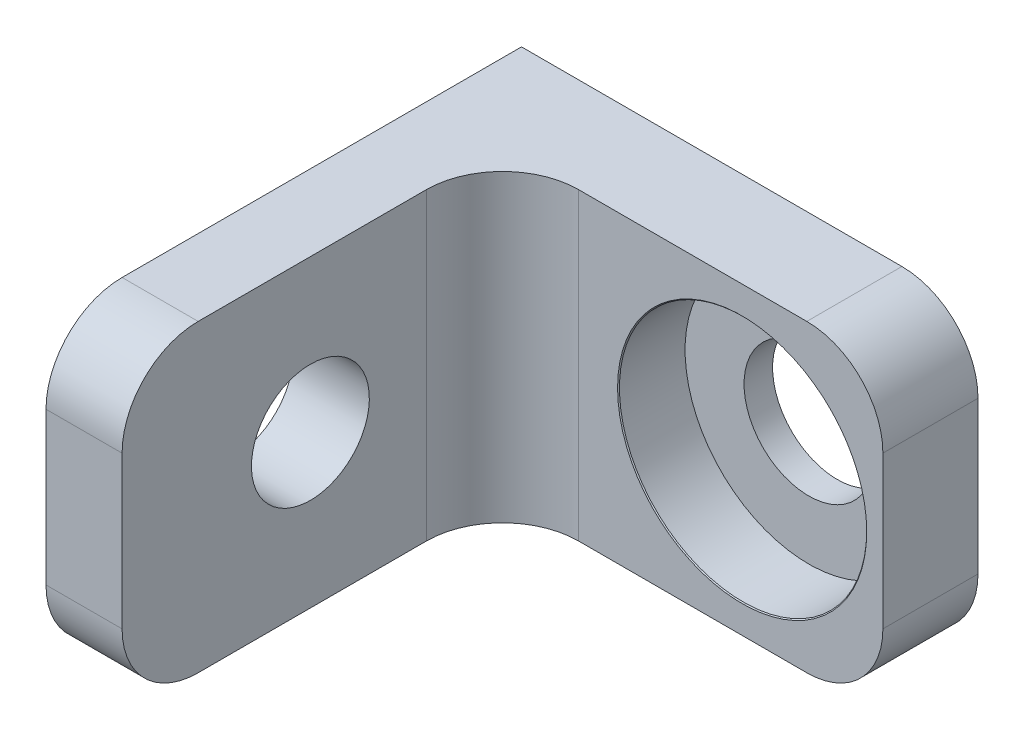
SolidWorks part; units mm, degrees
ref_plane "Plano frontal" through (0, 0, 0) normal (0, 0, 1) x (1, 0, 0)
ref_plane "Plano superior" through (0, 0, 0) normal (0, 1, 0) x (1, 0, 0)
ref_plane "Plano direito" through (0, 0, 0) normal (1, 0, 0) x (0, 0, -1)
sketch "Esboço1" plane through (0, 0, 0) normal (0, 0, 1) x (1, 0, 0)
  line L1 (-12, 6) -> (0, 6)
  line L2 (-12, 6) -> (-12, -2)
  line L3 (-12, -2) -> (0, -2)
  line L4 (0, 6) -> (0, -2)
  dimension "D1" = 8
  dimension "D2" = 12
extrude "Ressalto-extrusão1" add sketch "Esboço1" along normal blind 2.5
sketch "Esboço2" plane through (0, 0, 2.5) normal (0, 0, 1) x (1, 0, 0)
  line L0 (-12, 2) -> (0, 2) construction
  line L1 (-12, 6) -> (-12, -2) construction
  line L2 (0, -2) -> (0, 6) construction
  circle A0 centre (-3.7, 2) radius 1.7
  point P9 (-5.4, 2)
  dimension "D2" = 3.4
  dimension "D1" = 6.6
sketch "Esboço3" plane through (0, 0, 2.5) normal (0, 0, 1) x (1, 0, 0)
  line L0 (-12, -2) -> (0, -2) construction
  line L1 (-12, 6) -> (-10, 6)
  line L2 (-12, 6) -> (-12, -2)
  line L3 (-12, -2) -> (-10, -2)
  line L4 (-10, 6) -> (-10, -2)
  dimension "D1" = 2
extrude "Ressalto-extrusão2" add sketch "Esboço3" along normal blind 10
sketch "Esboço6" plane through (-10, 0, 0) normal (1, 0, 0) x (0, 0, -1)
  line L0 (-12.5, 2) -> (-2.5011, 2) construction
  line L1 (-12.5, -2) -> (-12.5, 6) construction
  line L2 (-2.5, -2) -> (-2.5, 6) construction
  circle A0 centre (-7.55, 2) radius 1.55
  point P6 (-6, 2)
  dimension "D2" = 3.1
  dimension "D1" = 3.5
hole_wizard "Rebaixo para parafuso com cabeça redonda de M33" positions "Esboço9" profile "Esboço10" counterbore size "M3" standard "ISO" end condition through all
sketch "Esboço9" plane through (0, 0, 2.5) normal (0, 0, 1) x (1, 0, 0)
  point P0 (-3.7, 2)
sketch "Esboço10" plane through (-3.7, 2, 2.5) normal (1, 0, 0) x (0, -1, 0)
  line L0 (0, 0) -> (0, 2.5)
  line L1 (0, 2.5) -> (1.7, 2.5)
  line L3 (1.7, 2.5) -> (1.7, 1.75)
  line L4 (3.25, 1.75) -> (1.7, 1.75)
  line L5 (3.25, 1.75) -> (3.25, 0.025)
  line L6 (3.25, 0.025) -> (3.275, 0)
  line L7 (3.275, 0) -> (0, 0)
  line L8 (-3.25, 0.025) -> (-3.275, 0) construction
  line L11 (0, -6.35) -> (0, 107.95) construction
  dimension "Thru Hole Dia." = 3.4
  dimension "Thru Hole Depth" = 2.5
  dimension "C'Bore Dia." = 6.5
  dimension "C'Bore Depth" = 1.75
  dimension "Near C'Sink Dia." = 6.55
  dimension "Near C'Sink Angle" = 90
fillet "Filete1" radius 2 1 edges at (-10, 2, 2.5)
fillet "Filete2" radius 2 4 edges at (0, 6, 1.25) (0, -2, 1.25) (-11, -2, 12.5) (-11, 6, 12.5)
extrude "Corte-extrusão2" cut sketch "Esboço6" against normal up to next
